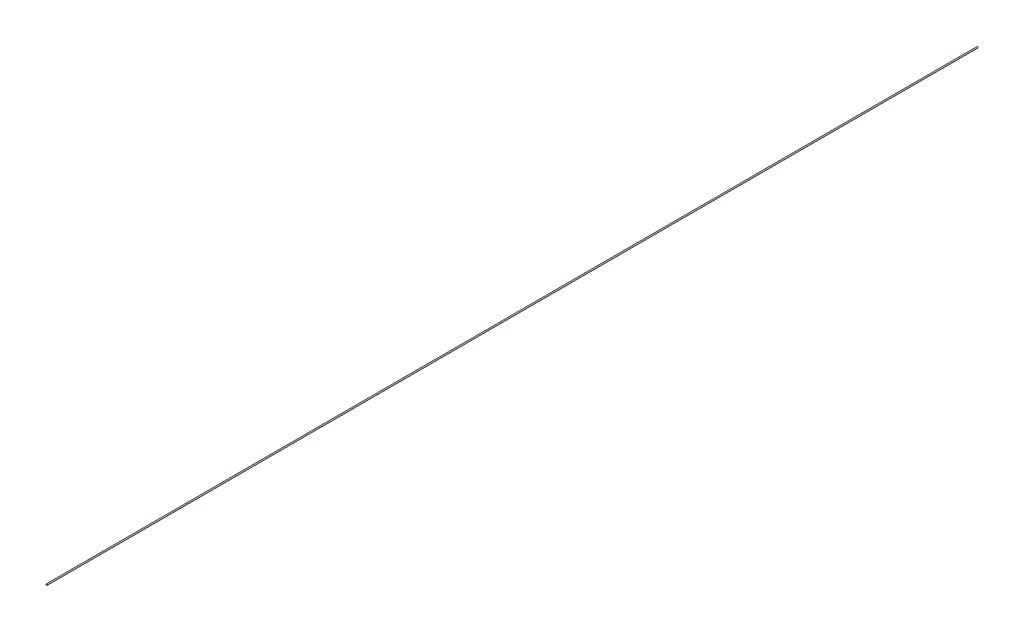
SolidWorks part; units mm, degrees
material "1060 Alloy"
ref_plane "Front Plane" through (0, 0, 0) normal (0, 0, 1) x (1, 0, 0)
ref_plane "Top Plane" through (0, 0, 0) normal (0, 1, 0) x (1, 0, 0)
ref_plane "Right Plane" through (0, 0, 0) normal (1, 0, 0) x (0, 0, -1)
sketch "Sketch1" plane through (0, 0, 0) normal (0, 0, 1) x (1, 0, 0)
  circle A0 centre (0, 0) radius 88.9
  circle A1 centre (0, 0) radius 50.8
  dimension "D1" = 177.8
  dimension "D2" = 101.6
extrude "Boss-Extrude1" add sketch "Sketch1" along normal blind 130356.864 contours A0 A1
equation "\"E\"= 8800000"
equation "\"Deformation\"= 0.009in"
equation "\"F\"= 400"
equation "\"Outer Diameter\"= 7in"
equation "\"Inner Diameter\"= 4in"
equation "\"Area\"= 25.92in"
equation "\"L\"= \"E\" * \"Deformation\" * \"Area\" / \"F\""
equation "\"D1@Sketch1\"=\"Outer Diameter\""
equation "\"D2@Sketch1\"=\"Inner Diameter\""
equation "\"D1@Boss-Extrude1\"=\"L\""
